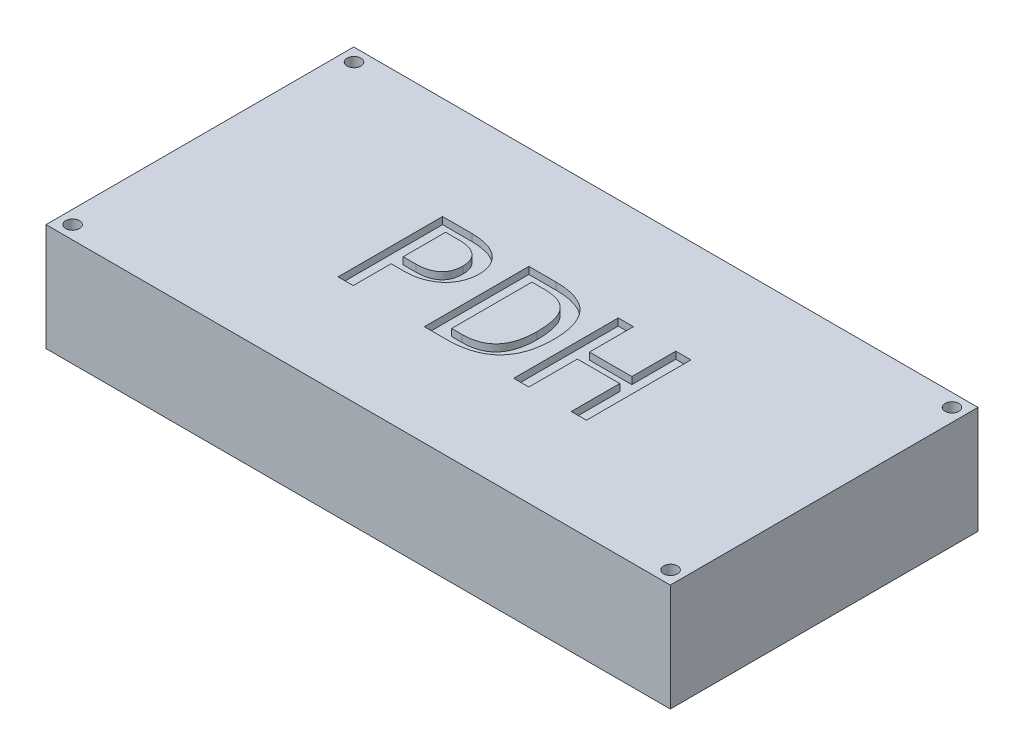
SolidWorks part; units mm, degrees
ref_plane "Front Plane" through (0, 0, 0) normal (0, 0, 1) x (1, 0, 0)
ref_plane "Top Plane" through (0, 0, 0) normal (0, 1, 0) x (1, 0, 0)
ref_plane "Right Plane" through (0, 0, 0) normal (1, 0, 0) x (0, 0, -1)
sketch "Sketch1" plane through (0, 0, 0) normal (0, 1, 0) x (1, 0, 0)
  line L1 (0, 0) -> (225.4, 0)
  line L2 (0, 0) -> (0, 111.1)
  line L3 (0, 111.1) -> (225.4, 111.1)
  line L4 (225.4, 0) -> (225.4, 111.1)
  line L5 (4.8, 106.4) -> (220.7, 106.4) construction
  line L6 (4.8, 106.4) -> (4.8, 4.8) construction
  line L7 (4.8, 4.8) -> (220.7, 4.8) construction
  line L8 (220.7, 106.4) -> (220.7, 4.8) construction
  circle A0 centre (4.8, 4.8) radius 2.5
  circle A1 centre (4.8, 106.4) radius 2.5
  circle A2 centre (220.7, 106.4) radius 2.5
  circle A3 centre (220.7, 4.8) radius 2.5
extrude "Boss-Extrude1" add sketch "Sketch1" along normal mid plane 38.7731
sketch "Sketch2" plane through (0, 19.3865, 0) normal (0, 1, 0) x (1, 0, 0)
  text T0 "PDH\r\n" font "Consolas" height in points 144
extrude "Cut-Extrude1" cut sketch "Sketch2" against normal blind 2.54
equation "\"D1@Sketch1\"=111.1mm"
equation "\"D2@Sketch1\"=225.4mm"
equation "\"D5@Sketch1\"=4.8mm"
equation "\"D3@Sketch1\"=5mm"
equation "\"D6@Sketch1\"=4.8mm"
